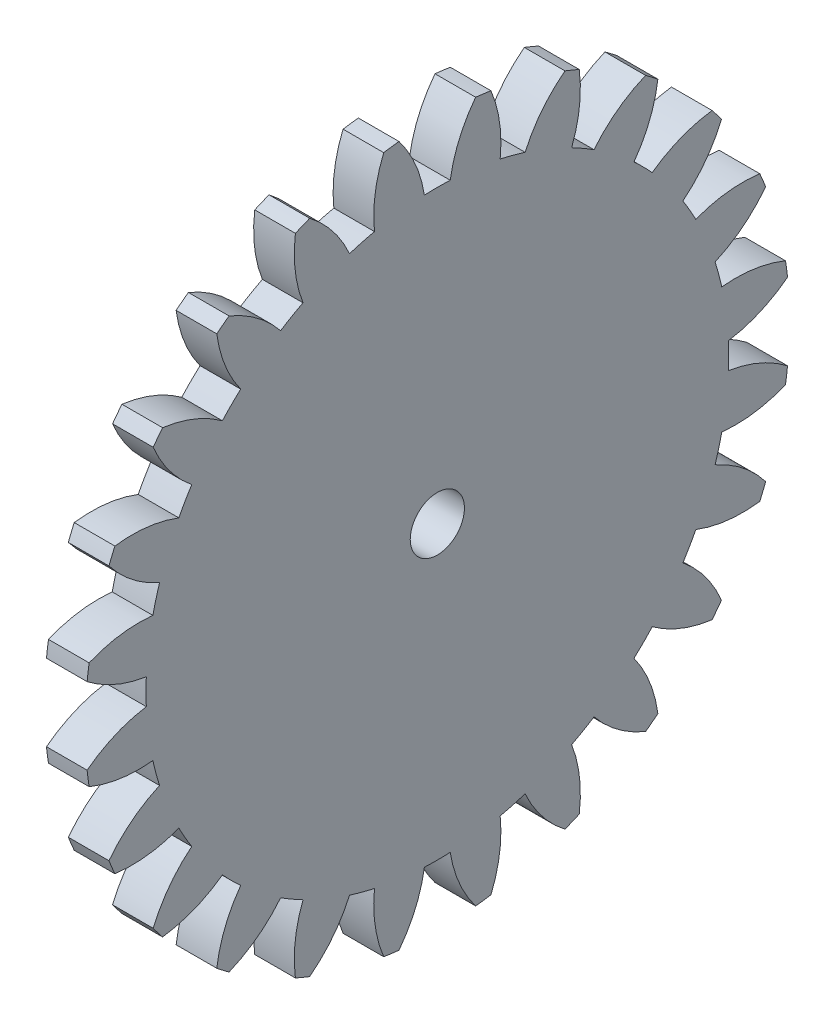
SolidWorks part; units mm, degrees
ref_plane "Plane1" through (0, 0, 0) normal (0, 0, 1) x (1, 0, 0)
ref_plane "Plane2" through (0, 0, 0) normal (0, 1, 0) x (1, 0, 0)
ref_plane "Plane3" through (0, 0, 0) normal (1, 0, 0) x (0, 0, -1)
sketch "HoldingSke" plane through (0, 0, 0) normal (0, 1, 0) x (1, 0, 0)
  line L0 (0, 0) -> (0.4568, -0.2034)
  line L1 (-15, 0) -> (100, 0) construction
  line L2 (0, 0) -> (-2.1039, 2.3779)
  line L3 (0, 0) -> (-11.863, 4.5341)
  line L4 (0, 0) -> (7.8894, 3.5126)
  line L5 (0, 0) -> (-46.8476, -17.4728)
  line L6 (0, 0) -> (-2.4869, -1.6779)
  line L7 (-2.1039, 2.3779) -> (8.6586, 51.2059)
  line L8 (-76.2, 54.61) -> (-75.5, 54.61)
  line L9 (-71.009, 38.7566) -> (-53.1078, 45.2721)
  line L10 (-76.2, 71.12) -> (104.1128, 71.12)
  line L11 (0, 0) -> (-3, 0)
  line L12 (-76.2, 101.6) -> (-76.133, 101.6)
  line L13 (24.9733, 27.94) -> (52.9518, 28.4284)
  line L14 (24.9733, 27.94) -> (24.9743, 27.94)
  line L15 (24.9733, 27.94) -> (100.4006, 29.5858)
  line L16 (-63.627, -2) -> (-12.827, -2)
  circle A0 centre (0, 0) radius 2
  circle A1 centre (0, 0) radius 21.499
  circle A2 centre (0, 0) radius 37.5
  circle A3 centre (0, 0) radius 2
  dimension "MHD" = 42.998
  dimension "Hub_dia" = 75
  dimension "Bore" = 4
  dimension "MBD" = 4
  dimension "Num_teeth" = 24
  dimension "Pitch" = 0.5
  dimension "Overall_len" = 50
  dimension "Show_teeth" = 24
  dimension "Thickness" = 3
  dimension "OAL" = 50.0001
  dimension "T_dim" = 0.7
  dimension "Ap" = 20
  dimension "H" = 19.05
  dimension "Pitch_radius" = 180.3128
  dimension "Width" = 3
  dimension "Backlash" = 0.067
  dimension "Addendum_fac" = 1
  dimension "Dedendum_fac" = 1.25
  dimension "Clearance_fac" = 0.25
  dimension "Dedendum_add" = 0.001
  dimension "Module" = 2
sketch "BasProSke" plane through (0, 0, 0) normal (0, 1, 0) x (1, 0, 0)
  line L0 (-10, 0) -> (60, 0) construction
  line L1 (0, 0) -> (0, 26)
  line L2 (0, 0) -> (3, 0)
  line L3 (3, 0) -> (3, 26)
  line L4 (3, 26) -> (0, 26)
  dimension "Thickness" = 3
  dimension "Diameter" = 52
revolve "Base-Revolve" add sketch "BasProSke" angle 360 about L0
sketch "TooCutSke" plane through (0, 0, 0) normal (1, 0, 0) x (0, 0, -1)
  line L1 (0, 0) -> (0, 107) construction
  line L2 (0, 0) -> (-1.6869, 23.9406) construction
  line L3 (0, 0) -> (-6.2538, 47.5021) construction
  line L4 (-1.6869, 23.9406) -> (-3.1269, 23.7511) construction
  arc A0 (0.9529, 21.4779) -> (-0.9529, 21.4779) centre (0, 0) ccw
  arc A1 (2.8465, 25.8693) -> (-2.8465, 25.8693) centre (0, 0) ccw
  circle A2 centre (0, 0) radius 24 construction
  circle A3 centre (0, 0) radius 22.5526 construction
  arc A4 (-0.9529, 21.4779) -> (-2.8465, 25.8693) centre (-10.4373, 19.9921) ccw
  arc A5 (2.8465, 25.8693) -> (0.9529, 21.4779) centre (10.4373, 19.9921) ccw
  dimension "Root_dia" = 42.998
  dimension "Overcut_dia" = 52.0508
  dimension "Pitch_dia" = 48
  dimension "Base_dia" = 45.1052
  dimension "Flank_rad" = 9.6
  dimension "Half_ang" = 7.5
  dimension "Half_CT" = 1.4524
extrude "ToothCut" cut sketch "TooCutSke" along normal through all
fillet "Breaks" [suppressed] radius 0.04
fillet "RootFillets" [suppressed] radius 0.501
pattern_circular "TeethCuts" count 24 every 15 about axis through (-10, 0, 0) along (1, 0, 0) of "ToothCut", "RootFillets", "Breaks"
sketch "HubNeaOneSke" plane through (0, 0, 0) normal (-1, 0, 0) x (0, 0, 1)
  circle A0 centre (0, 0) radius 21.499
  dimension "Diameter" = 42.998
extrude "HubNearOne" [suppressed] add sketch "HubNeaOneSke" along normal blind 47.0001
sketch "HubNeaBotSke" plane through (0, 0, 0) normal (-1, 0, 0) x (0, 0, 1)
  circle A0 centre (0, 0) radius 21.499
  dimension "Diameter" = 42.998
extrude "HubNearBoth" [suppressed] add sketch "HubNeaBotSke" along normal blind 23.5
ref_plane "FarPln" through (3, 0, 0) normal (1, 0, 0) x (0, 0, -1)
sketch "HubFarSke" plane through (3, 0, 0) normal (1, 0, 0) x (0, 0, -1)
  circle A0 centre (0, 0) radius 21.499
  dimension "Diameter" = 42.998
extrude "HubFar" [suppressed] add sketch "HubFarSke" along normal blind 23.5
sketch "BorSke" plane through (0, 0, 0) normal (1, 0, 0) x (0, 0, -1)
  circle A0 centre (0, 0) radius 2
  dimension "Diameter" = 4
extrude "Bore" cut sketch "BorSke" along normal mid plane 100.0001
sketch "KeySke" plane through (0, 0, 0) normal (1, 0, 0) x (0, 0, -1)
  line L0 (-0.8, 0) -> (-0.8, 2.7)
  line L1 (-0.8, 2.7) -> (0.8, 2.7)
  line L2 (0.8, 2.7) -> (0.8, 0)
  line L3 (0, 0) -> (0, 34) construction
  line L4 (-0.8, 0) -> (0.8, 0)
  dimension "Offset" = 2.7
  dimension "Width" = 1.6
extrude "Keyway" [suppressed] cut sketch "KeySke" along normal mid plane 100.0001
pattern_circular "Keyway2" [suppressed] count 2 every 90 about axis through (-10, 0, 0) along (1, 0, 0)
equation "' \"Module@HoldingSke\" = 6.35"
equation "' \"Num_teeth@HoldingSke\" = 12"
equation "' \"Ap@HoldingSke\" =  20"
equation "' \"Ap@HoldingSke\" = 20"
equation "' \"Width@HoldingSke\" = 0.5 * 25.4"
equation "' \"Hub_dia@HoldingSke\"= 1 * 25.4"
equation "' \"Hub_dia@HoldingSke\" = 1 * 25.4"
equation "' \"Overall_len@HoldingSke\" = 1.0 * 25.4"
equation "' \"Bore@HoldingSke\" = 0.75 * 25.4"
equation "' \"T_dim@HoldingSke\" = 0.1 * 25.4"
equation "' \"Width@KeySke\" = 0.25 * 25.4"
equation "' \"Show_teeth@HoldingSke\" = 13"
equation "' \"Backlash@HoldingSke\" = 0.009 * 25.4"
equation "' \"Addendum_fac@HoldingSke\" = 1.0"
equation "' \"Dedendum_fac@HoldingSke\" = 1.25"
equation "' \"Dedendum_add@HoldingSke\" = 0.00005 * 25.4"
equation "' \"Clearance_fac@HoldingSke\" = 0.25"
equation "\"Pitch@HoldingSke\" = 1 / \"Module@HoldingSke\""
equation "\"Overcut_dia@TooCutSke\" = (\"Num_teeth@HoldingSke\" + 2 * \"Addendum_fac@HoldingSke\") / \"Pitch@HoldingSke\" + 0.002 * 25.4"
equation "\"Pitch_dia@TooCutSke\" = \"Num_teeth@HoldingSke\" / \"Pitch@HoldingSke\""
equation "\"Base_dia@TooCutSke\" = \"Num_teeth@HoldingSke\" / \"Pitch@HoldingSke\" * cos((\"Ap@HoldingSke\"  * 3.14159265 / 180))"
equation "\"Root_dia@TooCutSke\" = (\"Num_teeth@HoldingSke\" + 2) / \"Pitch@HoldingSke\" - 2 * (\"Addendum_fac@HoldingSke\" + \"Dedendum_fac@HoldingSke\") / \"Pitch@HoldingSke\" - \"Dedendum_add@HoldingSke\" * 2"
equation "\"Half_ang@TooCutSke\" = 180 / \"Num_teeth@HoldingSke\""
equation "\"Half_CT@TooCutSke\" = \"Num_teeth@HoldingSke\" / \"Pitch@HoldingSke\" * sin((3.14159265 / 2 / \"Num_teeth@HoldingSke\")) / 2 - 7 * \"Backlash@HoldingSke\" / 4"
equation "\"Flank_rad@TooCutSke\" = \"Num_teeth@HoldingSke\" / \"Pitch@HoldingSke\" / 5"
equation "\"Radius@RootFillets\" = \"Clearance_fac@HoldingSke\" / \"Pitch@HoldingSke\" + \"Dedendum_add@HoldingSke\""
equation "\"Break_rad@Breaks\" = 0.02 / \"Pitch@HoldingSke\""
equation "\"Thickness@HoldingSke\" = \"Width@HoldingSke\""
equation "\"OAL@HoldingSke\" = \"Thickness@HoldingSke\""
equation "\"MHD@HoldingSke\" = (\"Num_teeth@HoldingSke\" + 2) / \"Pitch@HoldingSke\" - 2 * (\"Addendum_fac@HoldingSke\" + \"Dedendum_fac@HoldingSke\")  / \"Pitch@HoldingSke\" - \"Dedendum_add@HoldingSke\" * 2"
equation "\"MBD@HoldingSke\" = (\"Num_teeth@HoldingSke\" + 2) / \"Pitch@HoldingSke\" - 2 * (\"Addendum_fac@HoldingSke\" + \"Dedendum_fac@HoldingSke\")  / \"Pitch@HoldingSke\" - \"Dedendum_add@HoldingSke\" * 2 - 0.002 * 25.4"
equation "\"MHD@HoldingSke\" = ((sgn( \"MHD@HoldingSke\" - \"Hub_dia@HoldingSke\" )-1)*( \"MHD@HoldingSke\" - \"Hub_dia@HoldingSke\" ))/-2+ \"Hub_dia@HoldingSke\""
equation "\"MBD@HoldingSke\" = ((sgn( \"MBD@HoldingSke\" - \"Bore@HoldingSke\" )-1)*( \"MBD@HoldingSke\" - \"Bore@HoldingSke\" ))/-2+ \"Bore@HoldingSke\""
equation "\"OAL@HoldingSke\" = ((sgn( \"OAL@HoldingSke\" - \"Overall_len@HoldingSke\" )+1)*( \"OAL@HoldingSke\" - \"Overall_len@HoldingSke\" ))/2 + \"Overall_len@HoldingSke\" + 0.000002 * 25.4"
equation "\"Num_teeth@TeethCuts\" = int( \"Show_teeth@HoldingSke\" ) + 1"
equation "\"Num_teeth@TeethCuts\" = ((sgn( \"Num_teeth@TeethCuts\" - \"Num_teeth@HoldingSke\" )-1)*( \"Num_teeth@TeethCuts\" - \"Num_teeth@HoldingSke\" ))/-2+ \"Num_teeth@HoldingSke\""
equation "\"Num_teeth@TeethCuts\" = ((sgn( \"Num_teeth@TeethCuts\" - 2.0)+1)*( \"Num_teeth@TeethCuts\" - 2.0))/2 +2.0"
equation "\"Angle@TeethCuts\" = 360.0 / \"Num_teeth@HoldingSke\""
equation "\"Diameter@BasProSke\" = (\"Num_teeth@HoldingSke\" + 2 * \"Addendum_fac@HoldingSke\") / \"Pitch@HoldingSke\""
equation "\"Thickness@BasProSke\"  = \"Thickness@HoldingSke\""
equation "' \"Fillet_rad@BasProSke\" =  \"Thickness@HoldingSke\" * 0.05"
equation "' \"Fillet_rad@BasProSke\" = \"Thickness@HoldingSke\" * 0.05"
equation "\"MHD@HoldingSke\" = ((sgn( \"MHD@HoldingSke\" - \"Root_dia@TooCutSke\" )-1)*( \"MHD@HoldingSke\" - \"Root_dia@TooCutSke\" ))/-2+ \"Root_dia@TooCutSke\""
equation "\"Diameter@HubNeaOneSke\" = \"MHD@HoldingSke\""
equation "\"Length@HubNearOne\" = \"OAL@HoldingSke\" - \"Thickness@BasProSke\""
equation "\"Diameter@HubNeaBotSke\" = \"MHD@HoldingSke\""
equation "\"Length@HubNearBoth\" = ( \"OAL@HoldingSke\" - \"Thickness@BasProSke\" ) / 2.0"
equation "\"Thickness@FarPln\" = \"Thickness@BasProSke\""
equation "\"Diameter@HubFarSke\" = \"MHD@HoldingSke\""
equation "\"Length@HubFar\" = ( \"OAL@HoldingSke\" - \"Thickness@BasProSke\" ) / 2.0"
equation "\"Diameter@BorSke\" = \"MBD@HoldingSke\""
equation "\"D1@Bore\" = \"OAL@HoldingSke\" * 2.0"
equation "\"D1@Keyway\" = \"OAL@HoldingSke\" * 2.0"
equation "\"Offset@KeySke\" = \"T_dim@HoldingSke\" + \"MBD@HoldingSke\" / 2.0"
